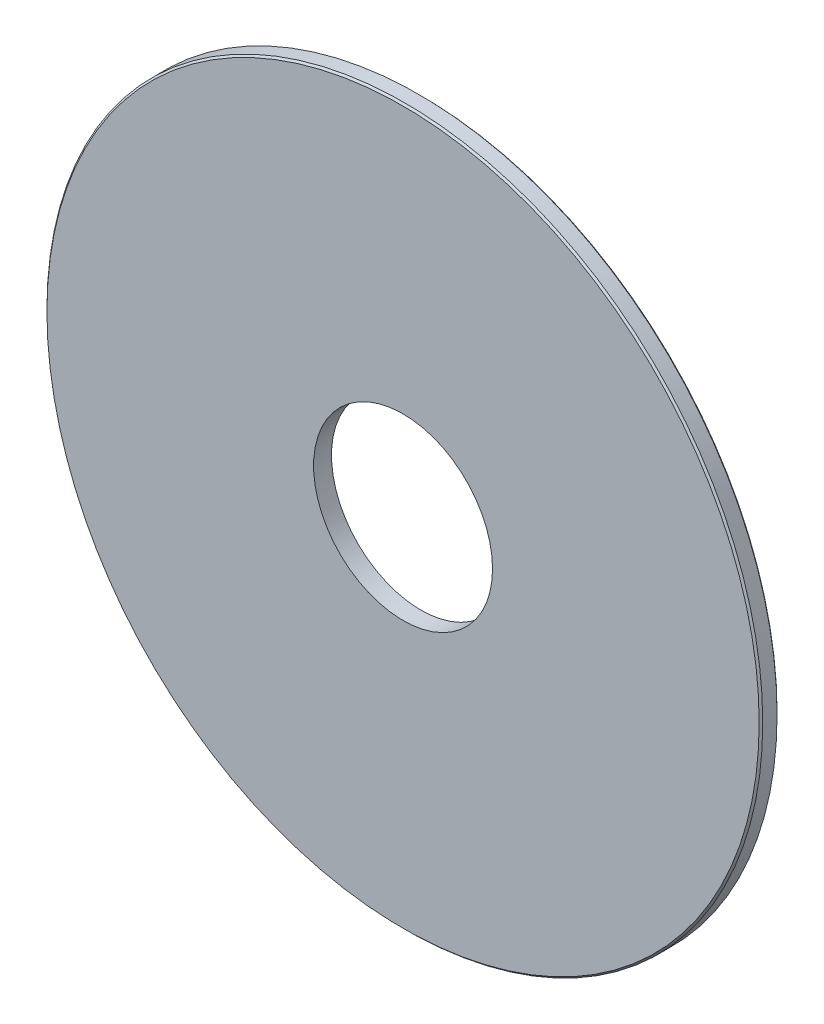
SolidWorks part; units mm, degrees
ref_plane "Front Plane" through (0, 0, 0) normal (0, 0, 1) x (1, 0, 0)
ref_plane "Top Plane" through (0, 0, 0) normal (0, 1, 0) x (1, 0, 0)
ref_plane "Right Plane" through (0, 0, 0) normal (1, 0, 0) x (0, 0, -1)
sketch "Sketch1" plane through (0, 0, 0) normal (0, 0, 1) x (1, 0, 0)
  circle A0 centre (0, 0) radius 10
  circle A1 centre (0, 0) radius 40
  dimension "D1" = 20
  dimension "D2" = 80
extrude "Boss-Extrude1" add sketch "Sketch1" along normal blind 2
chamfer "Chamfer1" distance 0.2 angle 45 2 edges at (40, 0, 0) (40, 0, 2)
